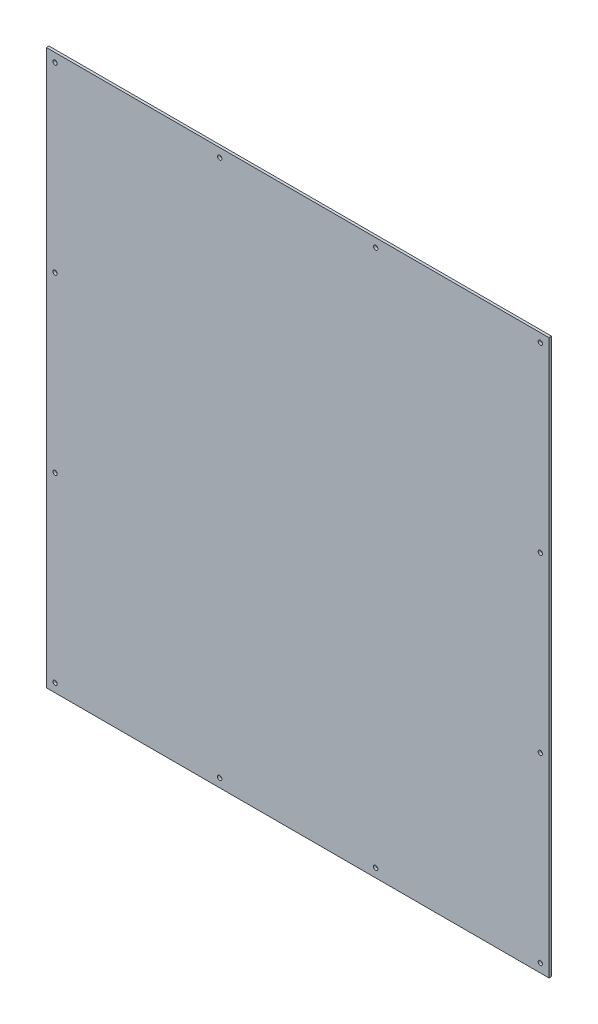
SolidWorks part; units mm, degrees
material "Acrylic (Medium-high impact)"
ref_plane "Front Plane" through (0, 0, 0) normal (0, 0, 1) x (1, 0, 0)
ref_plane "Top Plane" through (0, 0, 0) normal (0, 1, 0) x (1, 0, 0)
ref_plane "Right Plane" through (0, 0, 0) normal (1, 0, 0) x (0, 0, -1)
sketch "Sketch2" plane through (0, 0, 0) normal (0, 0, 1) x (1, 0, 0)
  line L1 (-219.5584, 289.0852) -> (360.4416, 289.0852)
  line L2 (-219.5584, 289.0852) -> (-219.5584, -350.9148)
  line L3 (-219.5584, -350.9148) -> (360.4416, -350.9148)
  line L4 (360.4416, 289.0852) -> (360.4416, -350.9148)
  dimension "D1" = 580
  dimension "D2" = 640
extrude "Boss-Extrude1" add sketch "Sketch2" along normal blind 3
sketch "Sketch3" plane through (0, 0, 3) normal (0, 0, 1) x (1, 0, 0)
  line L0 (360.4416, 289.0852) -> (-219.5584, 289.0852) construction
  line L1 (-219.5584, 289.0852) -> (-219.5584, -350.9148) construction
  line L2 (-219.5584, -350.9148) -> (360.4416, -350.9148) construction
  line L3 (360.4416, -350.9148) -> (360.4416, 289.0852) construction
  circle A0 centre (-209.5584, 279.0852) radius 2.5
  circle A1 centre (-209.5584, 69.0852) radius 2.5
  circle A2 centre (-209.5584, -340.9148) radius 2.5
  circle A3 centre (-209.5584, -130.9148) radius 2.5
  circle A4 centre (350.4416, 279.0852) radius 2.5
  circle A5 centre (350.4416, 69.0852) radius 2.5
  circle A6 centre (350.4416, -130.9148) radius 2.5
  circle A7 centre (350.4416, -340.9148) radius 2.5
  circle A8 centre (-19.5584, -340.9148) radius 2.5
  circle A9 centre (160.4416, -340.9148) radius 2.5
  circle A10 centre (-19.5584, 279.0852) radius 2.5
  circle A11 centre (160.4416, 279.0852) radius 2.5
  dimension "D1" = 5
  dimension "D3" = 10
  dimension "D4" = 10
  dimension "D5" = 10
  dimension "D6" = 210
  dimension "D7" = 210
  dimension "D8" = 10
  dimension "D9" = 10
  dimension "D10" = 5
  dimension "D12" = 10
  dimension "D13" = 5
  dimension "D16" = 5
  dimension "D17" = 200
  dimension "D19" = 5
  dimension "D20" = 10
  dimension "D21" = 10
  dimension "D22" = 5
  dimension "D24" = 5
  dimension "D25" = 190
  dimension "D26" = 10
  dimension "D27" = 5
  dimension "D28" = 10
  dimension "D29" = 190
  dimension "D30" = 5
  dimension "D31" = 180
  dimension "D32" = 10
  dimension "D33" = 10
  dimension "D2" = 10
  dimension "D11" = 10
  dimension "D14" = 210
  dimension "D15" = 10
  dimension "D18" = 10
  dimension "D23" = 190
extrude "Cut-Extrude1" cut sketch "Sketch3" against normal through all
